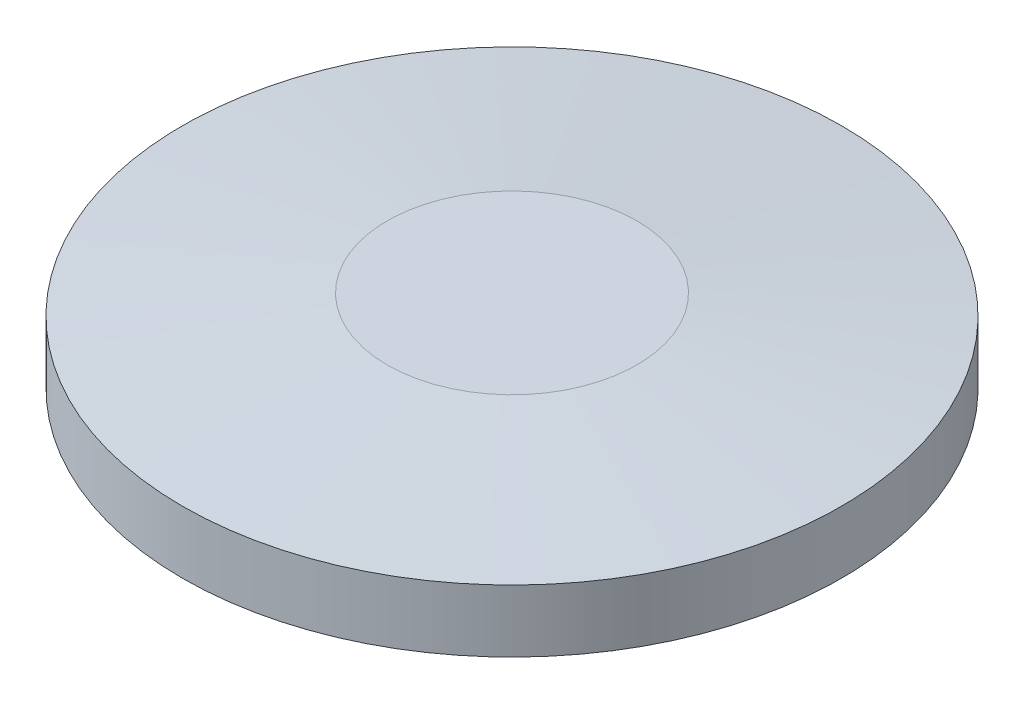
SolidWorks part; units mm, degrees
ref_plane "Front Plane" through (0, 0, 0) normal (0, 0, 1) x (1, 0, 0)
ref_plane "Top Plane" through (0, 0, 0) normal (0, 1, 0) x (1, 0, 0)
ref_plane "Right Plane" through (0, 0, 0) normal (1, 0, 0) x (0, 0, -1)
sketch "Sketch1" plane through (0, 0, 0) normal (1, 0, 0) x (0, 0, -1)
  line L0 (0, 0) -> (0, 4.7) construction
  line L2 (19.8, -0.25) -> (19.8, 3.5)
  line L3 (19.8, 3.5) -> (7.5, 4.7)
  line L4 (7.5, 4.7) -> (0, 4.7)
  line L5 (19.8, -0.25) -> (18.4, -0.25)
  line L6 (18.4, -0.25) -> (18.4, 0.25)
  line L7 (18.4, 0.25) -> (0, 0.25)
  line L8 (0, 0.25) -> (0, 4.7)
  dimension "D1" = 4.7
  dimension "D2" = 39.6
  dimension "D3" = 3.75
  dimension "D4" = 15
  dimension "D5" = 1.4
  dimension "D6" = 0.5
revolve "Revolve1" add sketch "Sketch1" angle 360 about L0
ref_plane "Plane1" through (0, 3.5, 0) normal (0, 1, 0) x (1, 0, 0)
sketch "Sketch2" plane through (0, 3.5, 0) normal (0, 1, 0) x (1, 0, 0)
  line L0 (0, -19.8) -> (0, 19.8) construction
  circle A0 centre (0, 0) radius 19.8 construction
sketch "Sketch3" plane through (0, 0, 0) normal (1, 0, 0) x (0, 0, -1)
  line L0 (19.8, 3.5) -> (24.1301, 1) construction
  line L1 (-19.8, 3.5) -> (19.8, 3.5) construction
  dimension "D1" = 150
  dimension "D2" = 5
